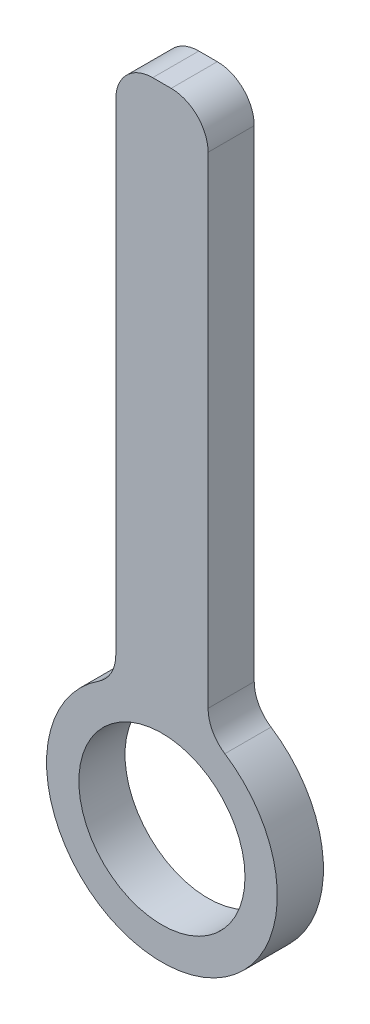
SolidWorks part; units mm, degrees
ref_plane "Front Plane" through (0, 0, 0) normal (0, 0, 1) x (1, 0, 0)
ref_plane "Top Plane" through (0, 0, 0) normal (0, 1, 0) x (1, 0, 0)
ref_plane "Right Plane" through (0, 0, 0) normal (1, 0, 0) x (0, 0, -1)
sketch "Sketch1" plane through (0, 0, 0) normal (0, 0, 1) x (1, 0, 0)
  line L0 (0, 0) -> (0, 79.1619) construction
  line L1 (-5, 13.8293) -> (-5, 66)
  line L2 (5, 13.8293) -> (5, 66)
  line L3 (-1, 70) -> (1, 70)
  circle A0 centre (0, 0) radius 9
  arc A1 (-6.8182, 10.4768) -> (6.8182, 10.4768) centre (0, 0) ccw
  arc A2 (5, 13.8293) -> (6.8182, 10.4768) centre (9, 13.8293) ccw
  arc A3 (-5, 13.8293) -> (-6.8182, 10.4768) centre (-9, 13.8293) cw
  arc A4 (5, 66) -> (1, 70) centre (1, 66) ccw
  arc A5 (-5, 66) -> (-1, 70) centre (-1, 66) cw
  point P10 (5, 11.4564)
  point P13 (-5, 11.4564)
  point P16 (5, 70)
  point P19 (-5, 70)
  dimension "D1" = 18
  dimension "D2" = 25
  dimension "D5" = 4
  dimension "D3" = 70
  dimension "D4" = 5
extrude "Boss-Extrude1" add sketch "Sketch1" along normal mid plane 5
sketch "Sketch2" plane through (0, 0, 2.5) normal (0, 0, 1) x (1, 0, 0)
  line L0 (-5, 61.4014) -> (5, 61.4014)
  line L3 (5, 13.8293) -> (5, 66)
  line L4 (1, 70) -> (-1, 70)
  line L5 (-5, 66) -> (-5, 13.8293)
  line L6 (5, 61.4014) -> (5, 66)
  line L7 (1, 70) -> (-1, 70)
  line L8 (-5, 66) -> (-5, 61.4014)
  arc A5 (5, 13.8293) -> (6.8182, 10.4768) centre (9, 13.8293) ccw
  arc A6 (5, 66) -> (1, 70) centre (1, 66) ccw
  arc A7 (-1, 70) -> (-5, 66) centre (-1, 66) ccw
  arc A8 (-6.8182, 10.4768) -> (-5, 13.8293) centre (-9, 13.8293) ccw
  arc A9 (-6.8182, 10.4768) -> (6.8182, 10.4768) centre (0, 0) ccw
  arc A10 (5, 13.8293) -> (6.8182, 10.4768) centre (9, 13.8293) ccw
  arc A11 (5, 66) -> (1, 70) centre (1, 66) ccw
  arc A12 (-1, 70) -> (-5, 66) centre (-1, 66) ccw
  arc A13 (-6.8182, 10.4768) -> (-5, 13.8293) centre (-9, 13.8293) ccw
  arc A14 (-6.8182, 10.4768) -> (6.8182, 10.4768) centre (0, 0) ccw
  line M10 (5, 13.8293) -> (5, 66)
  arc M11 (5, 66) -> (1, 70) centre (1, 66) ccw
  line M12 (1, 70) -> (-1, 70)
  arc M13 (-1, 70) -> (-5, 66) centre (-1, 66) ccw
  line M14 (-5, 66) -> (-5, 13.8293)
  dimension "D1" = 0
extrude "Boss-Extrude2" [suppressed] add sketch "Sketch2" along normal blind 131 contours L0 M14 M10 M11 M12 M13
ref_plane "Plane1" [suppressed] through (0, 0, 68) normal (0, 0, 1) x (1, 0, 0)
mirror "Mirror1" [suppressed] about plane through (0, 0, 68) normal (0, 0, 1)
